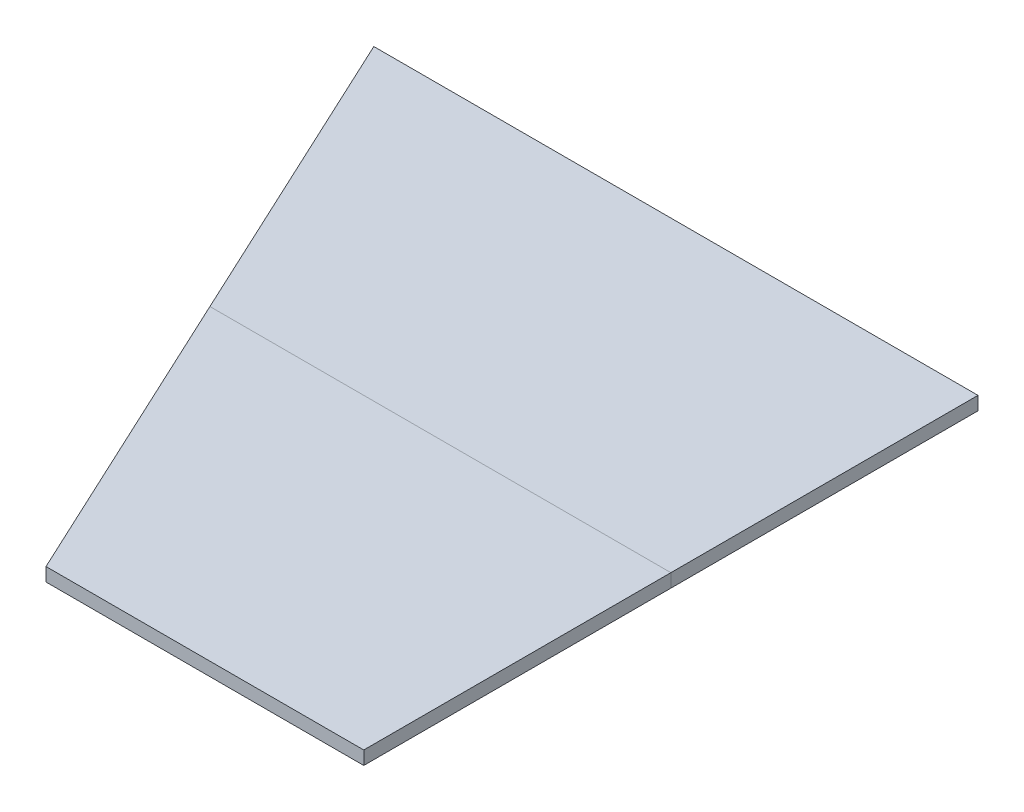
SolidWorks part; units mm, degrees
ref_plane "Front Plane" through (0, 0, 0) normal (0, 0, 1) x (1, 0, 0)
ref_plane "Top Plane" through (0, 0, 0) normal (0, 1, 0) x (1, 0, 0)
ref_plane "Right Plane" through (0, 0, 0) normal (1, 0, 0) x (0, 0, -1)
sketch "Sketch1" plane through (0, 0, 0) normal (0, 1, 0) x (1, 0, 0)
  line L1 (-90, 0) -> (90, 0)
  line L2 (-90, 0) -> (-4.6657, -183)
  line L9 (-4.6657, -183) -> (90, -183)
  line L10 (90, 0) -> (90, -183)
  point P4 (0, 0)
  dimension "D1" = 180
  dimension "D3" = 65
  dimension "D11" = 183
extrude "Boss-Extrude1" add sketch "Sketch1" along normal blind 4
ref_plane "Plane1" through (0, 0, 91.5) normal (0, 0, -1) x (-1, 0, 0)
sketch "Sketch2" plane through (0, 4, 0) normal (0, 1, 0) x (1, 0, 0)
  line L3 (-4.6657, -183) -> (90, -183) construction
  line L4 (-90, 0) -> (-4.6657, -183) construction
  line L5 (20, -183) -> (-4.6657, -183)
  line L6 (-4.6657, -183) -> (-39.614, -108.0531)
  spline S0 degree 3 poles (20, -183) (20, -169.1284) (16.2132, -139.1102) (-29.8657, -128.9584) (-39.614, -108.0531) knots 0 0 0 0 0.309774 1 1 1 1
  dimension "D1" = 70
extrude "Cut-Extrude2" [suppressed] cut sketch "Sketch2" against normal through all
split "Split1" trim tools "Plane1" bodies to split 101 113 resulting bodies 110 111
equation "\"arm length\"= 223"
